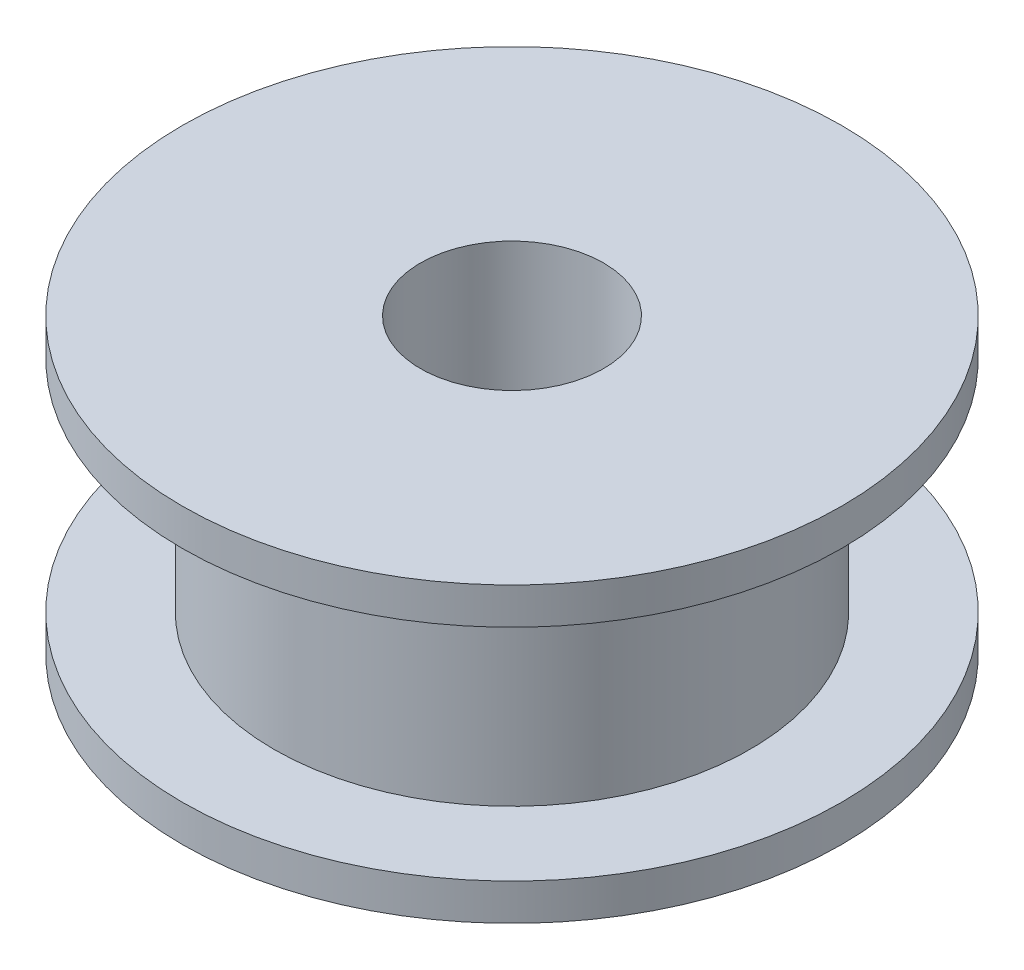
SolidWorks part; units mm, degrees
ref_plane "Płaszczyzna przednia" through (0, 0, 0) normal (0, 0, 1) x (1, 0, 0)
ref_plane "Płaszczyzna górna" through (0, 0, 0) normal (0, 1, 0) x (1, 0, 0)
ref_plane "Płaszczyzna prawa" through (0, 0, 0) normal (1, 0, 0) x (0, 0, -1)
sketch "Sketch1" plane through (0, 0, 0) normal (0, 0, 1) x (1, 0, 0)
  line L0 (0, 0) -> (0, 13.0429) construction
  line L1 (2.5, 0) -> (2.5, 8)
  line L2 (2.5, 8) -> (9, 8)
  line L3 (9, 8) -> (9, 7)
  line L4 (9, 7) -> (6.5, 7)
  line L5 (6.5, 7) -> (6.5, 1)
  line L6 (6.5, 1) -> (9, 1)
  line L7 (9, 1) -> (9, 0)
  line L8 (9, 0) -> (2.5, 0)
  dimension "D1" = 2.5
  dimension "D2" = 6.5
  dimension "D3" = 6.5
  dimension "D4" = 1
  dimension "D5" = 1
  dimension "D6" = 6
  dimension "D7" = 4
revolve "Revolve1" add sketch "Sketch1" angle 360 about L0
